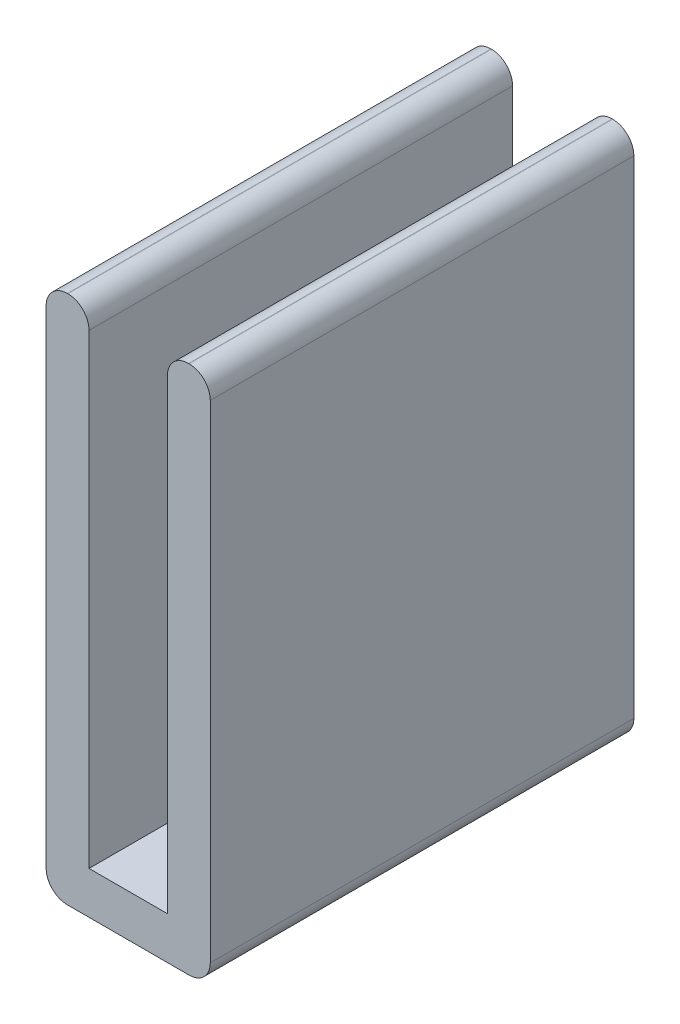
SolidWorks part; units mm, degrees
ref_plane "Front Plane" through (0, 0, 0) normal (0, 0, 1) x (1, 0, 0)
ref_plane "Top Plane" through (0, 0, 0) normal (0, 1, 0) x (1, 0, 0)
ref_plane "Right Plane" through (0, 0, 0) normal (1, 0, 0) x (0, 0, -1)
sketch "Sketch1" plane through (0, 0, 0) normal (0, 0, 1) x (1, 0, 0)
  line L0 (2.69, 10) -> (2.7, 10)
  line L1 (0.4, 0) -> (2.7, 0)
  line L2 (0, 0.4) -> (0, 9.6)
  line L3 (0.4, 10) -> (0.41, 10)
  line L4 (3.1, 0.4) -> (3.1, 9.6)
  line L6 (0.81, 9.6) -> (0.81, 0.8)
  line L7 (0.81, 0.8) -> (2.29, 0.8)
  line L8 (2.29, 9.6) -> (2.29, 0.8)
  arc A0 (2.7, 0) -> (3.1, 0.4) centre (2.7, 0.4) ccw
  arc A1 (0.4, 0) -> (0, 0.4) centre (0.4, 0.4) cw
  arc A2 (2.7, 10) -> (3.1, 9.6) centre (2.7, 9.6) cw
  arc A3 (2.69, 10) -> (2.29, 9.6) centre (2.69, 9.6) ccw
  arc A4 (0.41, 10) -> (0.81, 9.6) centre (0.41, 9.6) cw
  arc A5 (0, 9.6) -> (0.4, 10) centre (0.4, 9.6) cw
  point P22 (0, 0)
extrude "Boss-Extrude1" add sketch "Sketch1" along normal blind 8
